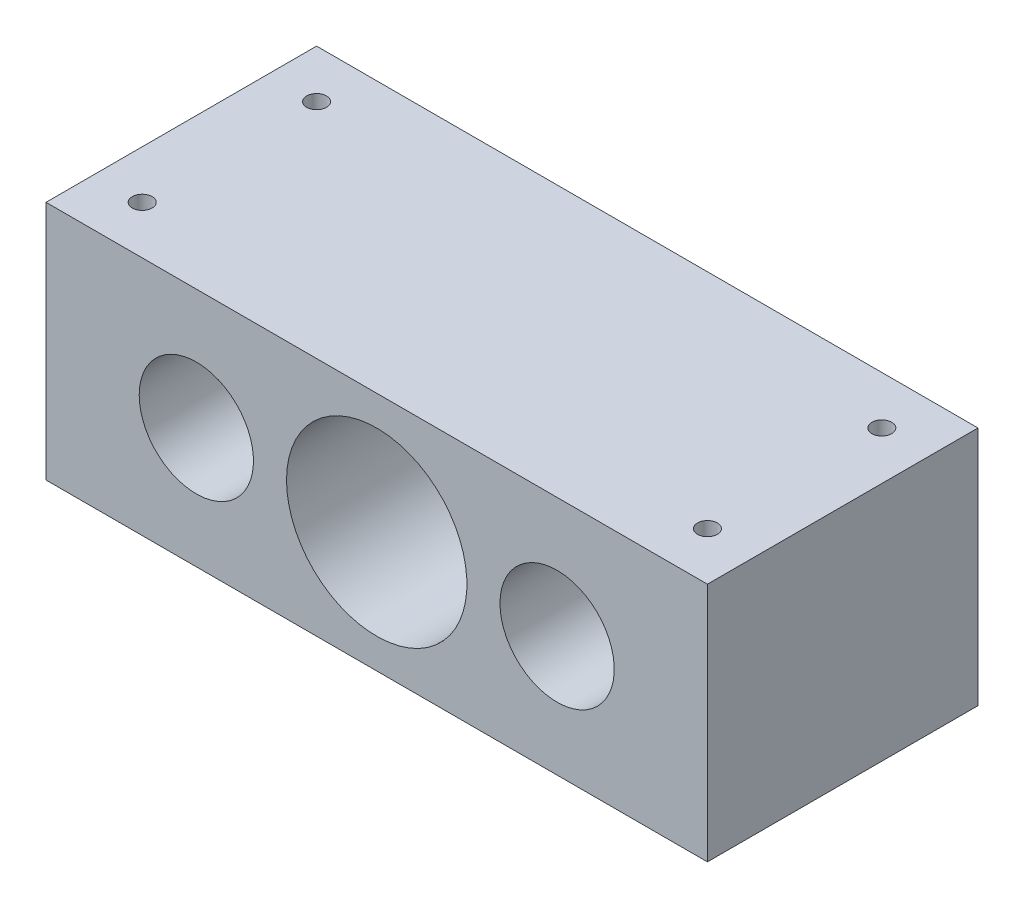
SolidWorks part; units mm, degrees
ref_plane "Alzado" through (0, 0, 0) normal (0, 0, 1) x (1, 0, 0)
ref_plane "Planta" through (0, 0, 0) normal (0, 1, 0) x (1, 0, 0)
ref_plane "Vista lateral" through (0, 0, 0) normal (1, 0, 0) x (0, 0, -1)
sketch "Sketch1" plane through (0, 0, 0) normal (0, 0, 1) x (1, 0, 0)
  line L0 (0, 0) -> (0, 40) construction
  line L1 (45, 40) -> (-45, 40)
  line L2 (-45, 40) -> (-45, 50)
  line L3 (45, 40) -> (45, 50)
  line L4 (-45, 50) -> (-55, 50)
  line L5 (45, 50) -> (55, 50)
  line L6 (-55, 50) -> (-55, 0)
  line L7 (55, 50) -> (55, 0)
  line L8 (-55, 0) -> (55, 0)
  line L9 (-55, 40) -> (-45, 40)
  line L10 (45, 40) -> (55, 40)
  circle A0 centre (-30, 20) radius 9.5
  circle A1 centre (30, 20) radius 9.5
  circle A2 centre (0, 20) radius 15
  point P6 (0, 40)
  point P12 (0, 0)
  point P28 (0, 20)
  dimension "D1" = 90
  dimension "D4" = 19
  dimension "D5" = 30
  dimension "D2" = 50
  dimension "D3" = 10
  dimension "D6" = 30
extrude "Boss-Extrude1" add sketch "Sketch1" along normal mid plane 45 contours L8 L0 A2 L1 L9 L6 A0 | L0 L8 L7 L10 L1 A2 A1
hole_wizard "M4 Tapped Hole1" positions "Sketch2" profile "Sketch3" tap size "M4" standard "DIN"
sketch "Sketch2" plane through (0, 0, -22.5) normal (0, 0, -1) x (-1, 0, 0)
  point P0 (12, 32)
  point P3 (-12, 32)
  point P6 (12, 8)
  point P9 (-12, 8)
sketch "Sketch3" plane through (-12, 32, -22.5) normal (1, 0, 0) x (0, 1, 0)
  line L0 (0, 0) -> (0, 11.0914)
  line L1 (0, 11.0914) -> (1.65, 10.1)
  line L2 (1.65, 10.1) -> (1.65, 0)
  line L5 (1.65, 0) -> (0, 0)
  line L10 (0, 11.0914) -> (-1.65, 10.1) construction
  line L11 (0, -6.35) -> (0, 107.95) construction
  dimension "Tap Drill Dia." = 3.3
  dimension "Tap Drill Depth" = 10.1
  dimension "Drill Angle" = 118
cosmetic thread "Hole Thread1" parameters "D1"=8, "D2"=4
cosmetic thread "Hole Thread2" parameters "D1"=8, "D2"=4
cosmetic thread "Hole Thread3" parameters "D1"=8, "D2"=4
cosmetic thread "Hole Thread4" parameters "D1"=8, "D2"=4
hole_wizard "M4 Tapped Hole2" positions "Sketch4" profile "Sketch5" tap size "M4" standard "DIN"
sketch "Sketch4" plane through (0, 40, 0) normal (0, 1, 0) x (1, 0, 0)
  line L2 (0, 0) -> (50000, 0) construction
  line L3 (0, 0) -> (47, 14.5) construction
  line L4 (47, 14.5) -> (-47, 14.5) construction
  line L5 (47, 14.5) -> (47, -14.5) construction
  point P0 (47, 14.5)
  point P74 (-47, 14.5)
  point P75 (-47, -14.5)
  point P76 (47, -14.5)
  dimension "D1" = 14.5
  dimension "D2" = 47
  dimension "D5" = 90
  dimension "D6" = 94
  dimension "D7" = 29
  dimension "D3" = 2
  dimension "D4" = 2
sketch "Sketch5" plane through (47, 40, -14.5) normal (1, 0, 0) x (0, 0, 1)
  line L0 (0, 0) -> (0, 15.9914)
  line L1 (0, 15.9914) -> (1.65, 15)
  line L2 (1.65, 15) -> (1.65, 0)
  line L5 (1.65, 0) -> (0, 0)
  line L10 (0, 15.9914) -> (-1.65, 15) construction
  line L11 (0, -6.35) -> (0, 107.95) construction
  dimension "Tap Drill Dia." = 3.3
  dimension "Tap Drill Depth" = 15
  dimension "Drill Angle" = 118
cosmetic thread "Hole Thread5" parameters "D1"=13, "D2"=4
cosmetic thread "Hole Thread6" parameters "D1"=13, "D2"=4
cosmetic thread "Hole Thread7" parameters "D1"=13, "D2"=4
cosmetic thread "Hole Thread10" parameters "D1"=13, "D2"=4
